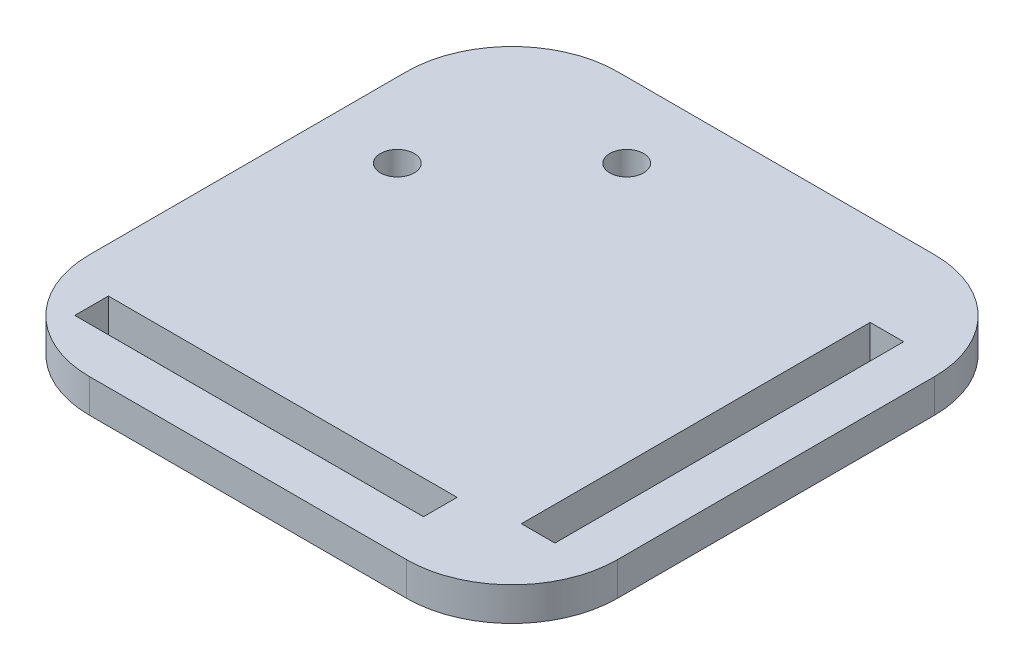
SolidWorks part; units mm, degrees
ref_plane "Front Plane" through (0, 0, 0) normal (0, 0, 1) x (1, 0, 0)
ref_plane "Top Plane" through (0, 0, 0) normal (0, 1, 0) x (1, 0, 0)
ref_plane "Right Plane" through (0, 0, 0) normal (1, 0, 0) x (0, 0, -1)
sketch "Sketch1" plane through (0, 0, 0) normal (0, 1, 0) x (1, 0, 0)
  line L1 (-25, 25) -> (25, 25)
  line L2 (-25, 25) -> (-25, -25)
  line L3 (-25, -25) -> (25, -25)
  line L4 (25, 25) -> (25, -25)
  line L5 (-25, 25) -> (25, -25) construction
  line L6 (-25, -25) -> (25, 25) construction
  point P0 (0, 0)
  dimension "D1" = 50
  dimension "D2" = 50
extrude "Boss-Extrude1" add sketch "Sketch1" along normal blind 3.175
sketch "Sketch2" plane through (0, 3.175, 0) normal (0, 1, 0) x (1, 0, 0)
  line L0 (-25, -25) -> (25, -25) construction
  line L1 (17.507, 16.402) -> (20.682, 16.402)
  line L2 (17.507, 16.402) -> (17.507, -16.618)
  line L3 (17.507, -16.618) -> (20.682, -16.618)
  line L4 (20.682, 16.402) -> (20.682, -16.618)
  line L5 (17.507, 16.402) -> (20.682, -16.618) construction
  line L6 (17.507, -16.618) -> (20.682, 16.402) construction
  line L7 (25, -25) -> (25, 25) construction
  line L8 (-20.72, -17.5) -> (12.3, -17.5)
  line L9 (-20.72, -17.5) -> (-20.72, -20.68)
  line L10 (-20.72, -20.68) -> (12.3, -20.68)
  line L11 (12.3, -17.5) -> (12.3, -20.68)
  line L12 (-20.72, -17.5) -> (12.3, -20.68) construction
  line L13 (-20.72, -20.68) -> (12.3, -17.5) construction
  point P0 (19.0945, -0.108)
  point P7 (-4.21, -19.09)
  dimension "D1" = 8.382
  dimension "D2" = 3.175
  dimension "D3" = 33.02
  dimension "D4" = 3.18
  dimension "D5" = 33.02
  dimension "D6" = 12.7
  dimension "D7" = 4.318
  dimension "D8" = 4.32
extrude "Cut-Extrude1" cut sketch "Sketch2" against normal through all
sketch "Sketch3" plane through (0, 3.175, 0) normal (0, 1, 0) x (1, 0, 0)
  line L0 (-25, 25) -> (-25, 0) construction
  line L1 (-25, 25) -> (-25, -25) construction
  line L2 (-25, 0) -> (0, 25) construction
  line L3 (25, 25) -> (-25, 25) construction
  line L4 (0, 25) -> (-25, 25) construction
  circle A0 centre (-7.0711, 17.9289) radius 1.6
  circle A1 centre (-17.9289, 7.0711) radius 1.6
  dimension "D4" = 3.2
  dimension "D1" = 25
  dimension "D2" = 10
  dimension "D3" = 10
extrude "Cut-Extrude2" cut sketch "Sketch3" against normal through all
fillet "Fillet1" radius 10 4 edges at (-25, 1.5875, -25) (-25, 1.5875, 25) (25, 1.5875, -25) (25, 1.5875, 25)
